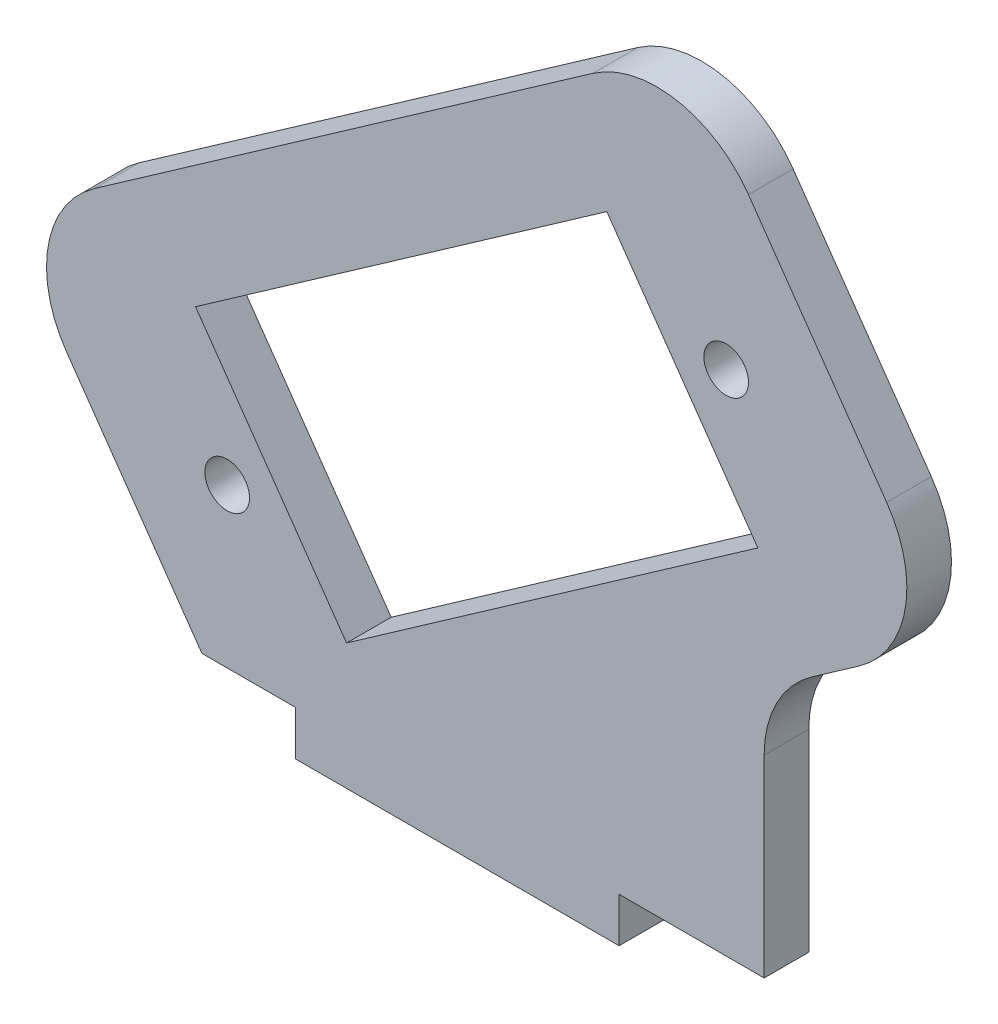
SolidWorks part; units mm, degrees
ref_plane "Front Plane" through (0, 0, 0) normal (0, 0, 1) x (1, 0, 0)
ref_plane "Top Plane" through (0, 0, 0) normal (0, 1, 0) x (1, 0, 0)
ref_plane "Right Plane" through (0, 0, 0) normal (1, 0, 0) x (0, 0, -1)
sketch "Sketch1" plane through (0, 0, 0) normal (0, 0, 1) x (1, 0, 0)
  line L1 (0, 0) -> (14.5, 0)
  line L16 (14.5, 0) -> (14.5, 2)
  line L17 (14.5, 2) -> (21, 2)
  line L18 (21, 2) -> (21, 10.6529)
  line L19 (23.1321, 14.7486) -> (25.2642, 16.2415)
  line L20 (26.492, 23.2051) -> (20.2974, 32.052)
  line L21 (13.3338, 33.2799) -> (-9.0291, 17.6212)
  line L22 (-10.257, 10.6576) -> (-4.1949, 2)
  line L23 (0, 0) -> (0, 2)
  line L24 (-4.482, 15.3116) -> (13.9489, 28.2171)
  line L25 (13.9489, 28.2171) -> (20.7171, 18.5511)
  line L26 (20.7171, 18.5511) -> (2.2862, 5.6456)
  line L27 (2.2862, 5.6456) -> (-4.482, 15.3116)
  line L28 (0, 2) -> (-4.1949, 2)
  line L30 (-3.0639, 9.102) -> (-1.0979, 10.4786) construction
  line L31 (17.333, 23.3841) -> (-1.0979, 10.4786) construction
  line L32 (17.333, 23.3841) -> (19.299, 24.7607) construction
  circle A7 centre (-3.0639, 9.102) radius 1
  circle A8 centre (19.299, 24.7607) radius 1
  circle A9 centre (12.5, 20) radius 2.6238 construction
  arc A10 (21, 10.6529) -> (23.1321, 14.7486) centre (26, 10.6529) cw
  arc A11 (25.2642, 16.2415) -> (26.492, 23.2051) centre (22.3963, 20.3373) ccw
  arc A12 (20.2974, 32.052) -> (13.3338, 33.2799) centre (16.2016, 29.1841) ccw
  arc A13 (-9.0291, 17.6212) -> (-10.257, 10.6576) centre (-6.1612, 13.5255) ccw
  dimension "D28" = 2
  dimension "D29" = 2
  dimension "D30" = 5
  dimension "D4" = 11.8
  dimension "D5" = 22.5
  dimension "D14" = 4.5
  dimension "D15" = 7.4
  dimension "D16" = 7.4
  dimension "D17" = 4.5
  dimension "D18" = 14.5
  dimension "D19" = 2.4
  dimension "D20" = 6.5
  dimension "D21" = 5.9
  dimension "D22" = 18
  dimension "D23" = 2
  dimension "D25" = 35
  dimension "D26" = 2
  dimension "D27" = 2.4
extrude "Boss-Extrude1" add sketch "Sketch1" along normal blind 2
